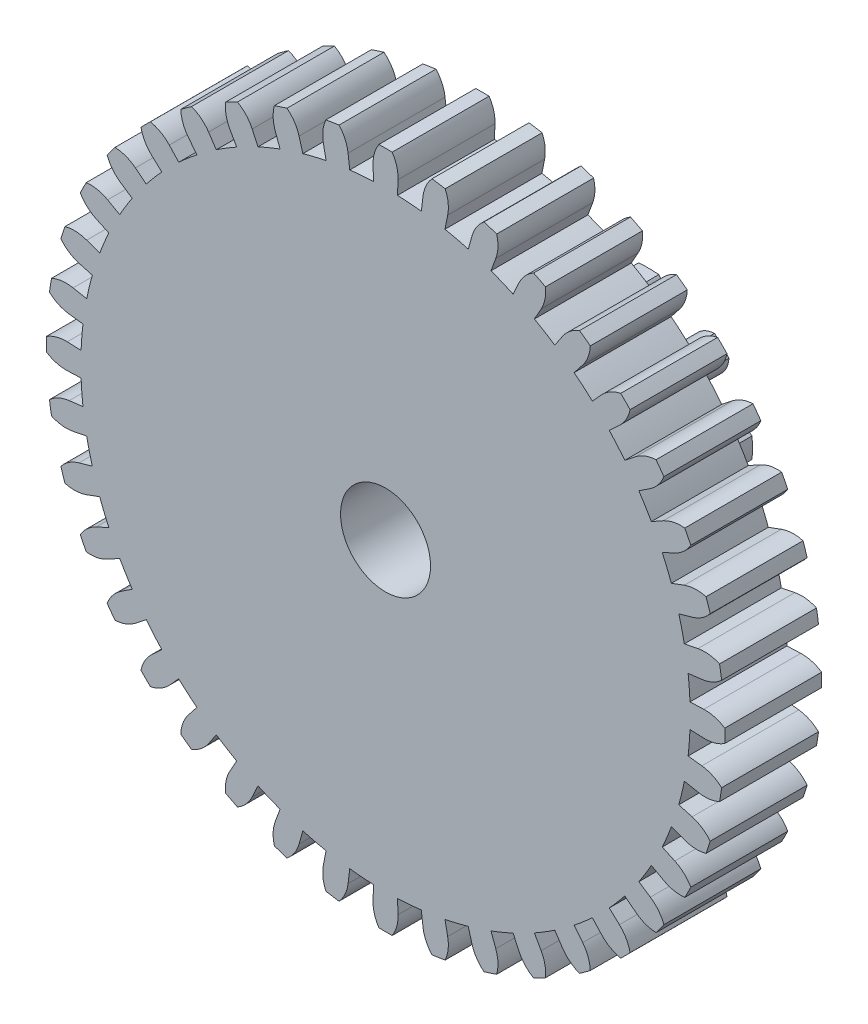
SolidWorks part; units mm, degrees
ref_plane "Front Plane" through (0, 0, 0) normal (0, 0, 1) x (1, 0, 0)
ref_plane "Top Plane" through (0, 0, 0) normal (0, 1, 0) x (1, 0, 0)
ref_plane "Right Plane" through (0, 0, 0) normal (1, 0, 0) x (0, 0, -1)
sketch "Sketch1" plane through (0, 0, 0) normal (0, 0, 1) x (1, 0, 0)
  line L0 (0, 0) -> (4.9, 0) construction
  line L1 (0, 0) -> (4.3864, 0.3452) construction
  line L2 (0, 0) -> (4.8962, 0.1924) construction
  line L3 (0, 0) -> (4.8991, 0.0962) construction
  line L4 (4.3966, 0.1727) -> (4.5965, 0.1806)
  line L5 (4.3966, -0.1727) -> (4.5965, -0.1806)
  line L6 (4.3695, -0.5172) -> (4.5681, -0.5407)
  line L7 (4.3155, -0.8584) -> (4.5116, -0.8974)
  line L8 (4.2348, -1.1943) -> (4.4273, -1.2486)
  line L9 (4.128, -1.5229) -> (4.3157, -1.5921)
  line L10 (3.9958, -1.8421) -> (4.1775, -1.9258)
  line L11 (3.839, -2.1499) -> (4.0135, -2.2477)
  line L12 (3.6585, -2.4445) -> (3.8248, -2.5556)
  line L13 (3.4554, -2.724) -> (3.6125, -2.8478)
  line L14 (3.231, -2.9867) -> (3.3779, -3.1225)
  line L15 (2.9867, -3.231) -> (3.1225, -3.3779)
  line L16 (2.724, -3.4554) -> (2.8478, -3.6125)
  line L17 (2.4445, -3.6585) -> (2.5556, -3.8248)
  line L18 (2.1499, -3.839) -> (2.2477, -4.0135)
  line L19 (1.8421, -3.9958) -> (1.9258, -4.1775)
  line L20 (1.5229, -4.128) -> (1.5921, -4.3157)
  line L21 (1.1943, -4.2348) -> (1.2486, -4.4273)
  line L22 (0.8584, -4.3155) -> (0.8974, -4.5116)
  line L23 (0.5172, -4.3695) -> (0.5407, -4.5681)
  line L24 (0.1727, -4.3966) -> (0.1806, -4.5965)
  line L25 (-0.1727, -4.3966) -> (-0.1806, -4.5965)
  line L26 (-0.5172, -4.3695) -> (-0.5407, -4.5681)
  line L27 (-0.8584, -4.3155) -> (-0.8974, -4.5116)
  line L28 (-1.1943, -4.2348) -> (-1.2486, -4.4273)
  line L29 (-1.5229, -4.128) -> (-1.5921, -4.3157)
  line L30 (-1.8421, -3.9958) -> (-1.9258, -4.1775)
  line L31 (-2.1499, -3.839) -> (-2.2477, -4.0135)
  line L32 (-2.4445, -3.6585) -> (-2.5556, -3.8248)
  line L33 (-2.724, -3.4554) -> (-2.8478, -3.6125)
  line L34 (-2.9867, -3.231) -> (-3.1225, -3.3779)
  line L35 (-3.231, -2.9867) -> (-3.3779, -3.1225)
  line L36 (-3.4554, -2.724) -> (-3.6125, -2.8478)
  line L37 (-3.6585, -2.4445) -> (-3.8248, -2.5556)
  line L38 (-3.839, -2.1499) -> (-4.0135, -2.2477)
  line L39 (-3.9958, -1.8421) -> (-4.1775, -1.9258)
  line L40 (-4.128, -1.5229) -> (-4.3157, -1.5921)
  line L41 (-4.2348, -1.1943) -> (-4.4273, -1.2486)
  line L42 (-4.3155, -0.8584) -> (-4.5116, -0.8974)
  line L43 (-4.3695, -0.5172) -> (-4.5681, -0.5407)
  line L44 (-4.3966, -0.1727) -> (-4.5965, -0.1806)
  line L45 (-4.3966, 0.1727) -> (-4.5965, 0.1806)
  line L46 (-4.3695, 0.5172) -> (-4.5681, 0.5407)
  line L47 (-4.3155, 0.8584) -> (-4.5116, 0.8974)
  line L48 (-4.2348, 1.1943) -> (-4.4273, 1.2486)
  line L49 (-4.128, 1.5229) -> (-4.3157, 1.5921)
  line L50 (-3.9958, 1.8421) -> (-4.1775, 1.9258)
  line L51 (-3.839, 2.1499) -> (-4.0135, 2.2477)
  line L52 (-3.6585, 2.4445) -> (-3.8248, 2.5556)
  line L53 (-3.4554, 2.724) -> (-3.6125, 2.8478)
  line L54 (-3.231, 2.9867) -> (-3.3779, 3.1225)
  line L55 (-2.9867, 3.231) -> (-3.1225, 3.3779)
  line L56 (-2.724, 3.4554) -> (-2.8478, 3.6125)
  line L57 (-2.4445, 3.6585) -> (-2.5556, 3.8248)
  line L58 (-2.1499, 3.839) -> (-2.2477, 4.0135)
  line L59 (-1.8421, 3.9958) -> (-1.9258, 4.1775)
  line L60 (-1.5229, 4.128) -> (-1.5921, 4.3157)
  line L61 (-1.1943, 4.2348) -> (-1.2486, 4.4273)
  line L62 (-0.8584, 4.3155) -> (-0.8974, 4.5116)
  line L63 (-0.5172, 4.3695) -> (-0.5407, 4.5681)
  line L64 (-0.1727, 4.3966) -> (-0.1806, 4.5965)
  line L65 (0.1727, 4.3966) -> (0.1806, 4.5965)
  line L66 (0.5172, 4.3695) -> (0.5407, 4.5681)
  line L67 (0.8584, 4.3155) -> (0.8974, 4.5116)
  line L68 (1.1943, 4.2348) -> (1.2486, 4.4273)
  line L69 (1.5229, 4.128) -> (1.5921, 4.3157)
  line L70 (1.8421, 3.9958) -> (1.9258, 4.1775)
  line L71 (2.1499, 3.839) -> (2.2477, 4.0135)
  line L72 (2.4445, 3.6585) -> (2.5556, 3.8248)
  line L73 (2.724, 3.4554) -> (2.8478, 3.6125)
  line L74 (2.9867, 3.231) -> (3.1225, 3.3779)
  line L75 (3.231, 2.9867) -> (3.3779, 3.1225)
  line L76 (3.4554, 2.724) -> (3.6125, 2.8478)
  line L77 (3.6585, 2.4445) -> (3.8248, 2.5556)
  line L78 (3.839, 2.1499) -> (4.0135, 2.2477)
  line L79 (3.9958, 1.8421) -> (4.1775, 1.9258)
  line L80 (4.128, 1.5229) -> (4.3157, 1.5921)
  line L81 (4.2348, 1.1943) -> (4.4273, 1.2486)
  line L82 (4.3155, 0.8584) -> (4.5116, 0.8974)
  line L83 (4.3695, 0.5172) -> (4.5681, 0.5407)
  arc A0 (4.8991, -0.0962) -> (4.8991, 0.0962) centre (0, 0) ccw
  circle A1 centre (0, 0) radius 4.6 construction
  circle A2 centre (0, 0) radius 4.4 construction
  arc A3 (4.8991, 0.0962) -> (4.5965, 0.1806) centre (4.6166, -0.3319) ccw
  circle A4 centre (0, 0) radius 4.9 construction
  arc A5 (4.3864, 0.3452) -> (4.3966, 0.1727) centre (0, 0) cw
  arc A6 (4.3864, -0.3452) -> (4.3966, -0.1727) centre (0, 0) ccw
  arc A7 (4.8991, -0.0962) -> (4.5965, -0.1806) centre (4.6166, 0.3319) cw
  arc A8 (4.3864, -0.3452) -> (4.3695, -0.5172) centre (0, 0) cw
  arc A9 (4.8538, -0.6714) -> (4.5681, -0.5407) centre (4.5078, -1.05) ccw
  arc A10 (4.8237, -0.8614) -> (4.8538, -0.6714) centre (0, 0) ccw
  arc A11 (4.8237, -0.8614) -> (4.5116, -0.8974) centre (4.6117, -0.3944) cw
  arc A12 (4.2784, -1.0272) -> (4.3155, -0.8584) centre (0, 0) ccw
  arc A13 (4.2784, -1.0272) -> (4.2348, -1.1943) centre (0, 0) cw
  arc A14 (4.689, -1.4224) -> (4.4273, -1.2486) centre (4.2881, -1.7423) ccw
  arc A15 (4.6295, -1.6054) -> (4.689, -1.4224) centre (0, 0) ccw
  arc A16 (4.6295, -1.6054) -> (4.3157, -1.5921) centre (4.4932, -1.1109) cw
  arc A17 (4.0651, -1.6838) -> (4.128, -1.5229) centre (0, 0) ccw
  arc A18 (4.0651, -1.6838) -> (3.9958, -1.8421) centre (0, 0) cw
  arc A19 (4.4088, -2.1384) -> (4.1775, -1.9258) centre (3.9627, -2.3916) ccw
  arc A20 (4.3214, -2.3098) -> (4.4088, -2.1384) centre (0, 0) ccw
  arc A21 (4.3214, -2.3098) -> (4.0135, -2.2477) centre (4.2641, -1.8001) cw
  arc A22 (3.7516, -2.299) -> (3.839, -2.1499) centre (0, 0) ccw
  arc A23 (3.7516, -2.299) -> (3.6585, -2.4445) centre (0, 0) cw
  arc A24 (4.02, -2.8018) -> (3.8248, -2.5556) centre (3.5398, -2.9821) ccw
  arc A25 (3.9069, -2.9574) -> (4.02, -2.8018) centre (0, 0) ccw
  arc A26 (3.9069, -2.9574) -> (3.6125, -2.8478) centre (3.93, -2.445) cw
  arc A27 (3.3458, -2.8576) -> (3.4554, -2.724) centre (0, 0) ccw
  arc A28 (3.3458, -2.8576) -> (3.231, -2.9867) centre (0, 0) cw
  arc A29 (3.5322, -3.3961) -> (3.3779, -3.1225) centre (3.0297, -3.4991) ccw
  arc A30 (3.3961, -3.5322) -> (3.5322, -3.3961) centre (0, 0) ccw
  arc A31 (3.3961, -3.5322) -> (3.1225, -3.3779) centre (3.4991, -3.0297) cw
  arc A32 (2.8576, -3.3458) -> (2.9867, -3.231) centre (0, 0) ccw
  arc A33 (2.8576, -3.3458) -> (2.724, -3.4554) centre (0, 0) cw
  arc A34 (2.9574, -3.9069) -> (2.8478, -3.6125) centre (2.445, -3.93) ccw
  arc A35 (2.8018, -4.02) -> (2.9574, -3.9069) centre (0, 0) ccw
  arc A36 (2.8018, -4.02) -> (2.5556, -3.8248) centre (2.9821, -3.5398) cw
  arc A37 (2.299, -3.7516) -> (2.4445, -3.6585) centre (0, 0) ccw
  arc A38 (2.299, -3.7516) -> (2.1499, -3.839) centre (0, 0) cw
  arc A39 (2.3098, -4.3214) -> (2.2477, -4.0135) centre (1.8001, -4.2641) ccw
  arc A40 (2.1384, -4.4088) -> (2.3098, -4.3214) centre (0, 0) ccw
  arc A41 (2.1384, -4.4088) -> (1.9258, -4.1775) centre (2.3916, -3.9627) cw
  arc A42 (1.6838, -4.0651) -> (1.8421, -3.9958) centre (0, 0) ccw
  arc A43 (1.6838, -4.0651) -> (1.5229, -4.128) centre (0, 0) cw
  arc A44 (1.6054, -4.6295) -> (1.5921, -4.3157) centre (1.1109, -4.4932) ccw
  arc A45 (1.4224, -4.689) -> (1.6054, -4.6295) centre (0, 0) ccw
  arc A46 (1.4224, -4.689) -> (1.2486, -4.4273) centre (1.7423, -4.2881) cw
  arc A47 (1.0272, -4.2784) -> (1.1943, -4.2348) centre (0, 0) ccw
  arc A48 (1.0272, -4.2784) -> (0.8584, -4.3155) centre (0, 0) cw
  arc A49 (0.8614, -4.8237) -> (0.8974, -4.5116) centre (0.3944, -4.6117) ccw
  arc A50 (0.6714, -4.8538) -> (0.8614, -4.8237) centre (0, 0) ccw
  arc A51 (0.6714, -4.8538) -> (0.5407, -4.5681) centre (1.05, -4.5078) cw
  arc A52 (0.3452, -4.3864) -> (0.5172, -4.3695) centre (0, 0) ccw
  arc A53 (0.3452, -4.3864) -> (0.1727, -4.3966) centre (0, 0) cw
  arc A54 (0.0962, -4.8991) -> (0.1806, -4.5965) centre (-0.3319, -4.6166) ccw
  arc A55 (-0.0962, -4.8991) -> (0.0962, -4.8991) centre (0, 0) ccw
  arc A56 (-0.0962, -4.8991) -> (-0.1806, -4.5965) centre (0.3319, -4.6166) cw
  arc A57 (-0.3452, -4.3864) -> (-0.1727, -4.3966) centre (0, 0) ccw
  arc A58 (-0.3452, -4.3864) -> (-0.5172, -4.3695) centre (0, 0) cw
  arc A59 (-0.6714, -4.8538) -> (-0.5407, -4.5681) centre (-1.05, -4.5078) ccw
  arc A60 (-0.8614, -4.8237) -> (-0.6714, -4.8538) centre (0, 0) ccw
  arc A61 (-0.8614, -4.8237) -> (-0.8974, -4.5116) centre (-0.3944, -4.6117) cw
  arc A62 (-1.0272, -4.2784) -> (-0.8584, -4.3155) centre (0, 0) ccw
  arc A63 (-1.0272, -4.2784) -> (-1.1943, -4.2348) centre (0, 0) cw
  arc A64 (-1.4224, -4.689) -> (-1.2486, -4.4273) centre (-1.7423, -4.2881) ccw
  arc A65 (-1.6054, -4.6295) -> (-1.4224, -4.689) centre (0, 0) ccw
  arc A66 (-1.6054, -4.6295) -> (-1.5921, -4.3157) centre (-1.1109, -4.4932) cw
  arc A67 (-1.6838, -4.0651) -> (-1.5229, -4.128) centre (0, 0) ccw
  arc A68 (-1.6838, -4.0651) -> (-1.8421, -3.9958) centre (0, 0) cw
  arc A69 (-2.1384, -4.4088) -> (-1.9258, -4.1775) centre (-2.3916, -3.9627) ccw
  arc A70 (-2.3098, -4.3214) -> (-2.1384, -4.4088) centre (0, 0) ccw
  arc A71 (-2.3098, -4.3214) -> (-2.2477, -4.0135) centre (-1.8001, -4.2641) cw
  arc A72 (-2.299, -3.7516) -> (-2.1499, -3.839) centre (0, 0) ccw
  arc A73 (-2.299, -3.7516) -> (-2.4445, -3.6585) centre (0, 0) cw
  arc A74 (-2.8018, -4.02) -> (-2.5556, -3.8248) centre (-2.9821, -3.5398) ccw
  arc A75 (-2.9574, -3.9069) -> (-2.8018, -4.02) centre (0, 0) ccw
  arc A76 (-2.9574, -3.9069) -> (-2.8478, -3.6125) centre (-2.445, -3.93) cw
  arc A77 (-2.8576, -3.3458) -> (-2.724, -3.4554) centre (0, 0) ccw
  arc A78 (-2.8576, -3.3458) -> (-2.9867, -3.231) centre (0, 0) cw
  arc A79 (-3.3961, -3.5322) -> (-3.1225, -3.3779) centre (-3.4991, -3.0297) ccw
  arc A80 (-3.5322, -3.3961) -> (-3.3961, -3.5322) centre (0, 0) ccw
  arc A81 (-3.5322, -3.3961) -> (-3.3779, -3.1225) centre (-3.0297, -3.4991) cw
  arc A82 (-3.3458, -2.8576) -> (-3.231, -2.9867) centre (0, 0) ccw
  arc A83 (-3.3458, -2.8576) -> (-3.4554, -2.724) centre (0, 0) cw
  arc A84 (-3.9069, -2.9574) -> (-3.6125, -2.8478) centre (-3.93, -2.445) ccw
  arc A85 (-4.02, -2.8018) -> (-3.9069, -2.9574) centre (0, 0) ccw
  arc A86 (-4.02, -2.8018) -> (-3.8248, -2.5556) centre (-3.5398, -2.9821) cw
  arc A87 (-3.7516, -2.299) -> (-3.6585, -2.4445) centre (0, 0) ccw
  arc A88 (-3.7516, -2.299) -> (-3.839, -2.1499) centre (0, 0) cw
  arc A89 (-4.3214, -2.3098) -> (-4.0135, -2.2477) centre (-4.2641, -1.8001) ccw
  arc A90 (-4.4088, -2.1384) -> (-4.3214, -2.3098) centre (0, 0) ccw
  arc A91 (-4.4088, -2.1384) -> (-4.1775, -1.9258) centre (-3.9627, -2.3916) cw
  arc A92 (-4.0651, -1.6838) -> (-3.9958, -1.8421) centre (0, 0) ccw
  arc A93 (-4.0651, -1.6838) -> (-4.128, -1.5229) centre (0, 0) cw
  arc A94 (-4.6295, -1.6054) -> (-4.3157, -1.5921) centre (-4.4932, -1.1109) ccw
  arc A95 (-4.689, -1.4224) -> (-4.6295, -1.6054) centre (0, 0) ccw
  arc A96 (-4.689, -1.4224) -> (-4.4273, -1.2486) centre (-4.2881, -1.7423) cw
  arc A97 (-4.2784, -1.0272) -> (-4.2348, -1.1943) centre (0, 0) ccw
  arc A98 (-4.2784, -1.0272) -> (-4.3155, -0.8584) centre (0, 0) cw
  arc A99 (-4.8237, -0.8614) -> (-4.5116, -0.8974) centre (-4.6117, -0.3944) ccw
  arc A100 (-4.8538, -0.6714) -> (-4.8237, -0.8614) centre (0, 0) ccw
  arc A101 (-4.8538, -0.6714) -> (-4.5681, -0.5407) centre (-4.5078, -1.05) cw
  arc A102 (-4.3864, -0.3452) -> (-4.3695, -0.5172) centre (0, 0) ccw
  arc A103 (-4.3864, -0.3452) -> (-4.3966, -0.1727) centre (0, 0) cw
  arc A104 (-4.8991, -0.0962) -> (-4.5965, -0.1806) centre (-4.6166, 0.3319) ccw
  arc A105 (-4.8991, 0.0962) -> (-4.8991, -0.0962) centre (0, 0) ccw
  arc A106 (-4.8991, 0.0962) -> (-4.5965, 0.1806) centre (-4.6166, -0.3319) cw
  arc A107 (-4.3864, 0.3452) -> (-4.3966, 0.1727) centre (0, 0) ccw
  arc A108 (-4.3864, 0.3452) -> (-4.3695, 0.5172) centre (0, 0) cw
  arc A109 (-4.8538, 0.6714) -> (-4.5681, 0.5407) centre (-4.5078, 1.05) ccw
  arc A110 (-4.8237, 0.8614) -> (-4.8538, 0.6714) centre (0, 0) ccw
  arc A111 (-4.8237, 0.8614) -> (-4.5116, 0.8974) centre (-4.6117, 0.3944) cw
  arc A112 (-4.2784, 1.0272) -> (-4.3155, 0.8584) centre (0, 0) ccw
  arc A113 (-4.2784, 1.0272) -> (-4.2348, 1.1943) centre (0, 0) cw
  arc A114 (-4.689, 1.4224) -> (-4.4273, 1.2486) centre (-4.2881, 1.7423) ccw
  arc A115 (-4.6295, 1.6054) -> (-4.689, 1.4224) centre (0, 0) ccw
  arc A116 (-4.6295, 1.6054) -> (-4.3157, 1.5921) centre (-4.4932, 1.1109) cw
  arc A117 (-4.0651, 1.6838) -> (-4.128, 1.5229) centre (0, 0) ccw
  arc A118 (-4.0651, 1.6838) -> (-3.9958, 1.8421) centre (0, 0) cw
  arc A119 (-4.4088, 2.1384) -> (-4.1775, 1.9258) centre (-3.9627, 2.3916) ccw
  arc A120 (-4.3214, 2.3098) -> (-4.4088, 2.1384) centre (0, 0) ccw
  arc A121 (-4.3214, 2.3098) -> (-4.0135, 2.2477) centre (-4.2641, 1.8001) cw
  arc A122 (-3.7516, 2.299) -> (-3.839, 2.1499) centre (0, 0) ccw
  arc A123 (-3.7516, 2.299) -> (-3.6585, 2.4445) centre (0, 0) cw
  arc A124 (-4.02, 2.8018) -> (-3.8248, 2.5556) centre (-3.5398, 2.9821) ccw
  arc A125 (-3.9069, 2.9574) -> (-4.02, 2.8018) centre (0, 0) ccw
  arc A126 (-3.9069, 2.9574) -> (-3.6125, 2.8478) centre (-3.93, 2.445) cw
  arc A127 (-3.3458, 2.8576) -> (-3.4554, 2.724) centre (0, 0) ccw
  arc A128 (-3.3458, 2.8576) -> (-3.231, 2.9867) centre (0, 0) cw
  arc A129 (-3.5322, 3.3961) -> (-3.3779, 3.1225) centre (-3.0297, 3.4991) ccw
  arc A130 (-3.3961, 3.5322) -> (-3.5322, 3.3961) centre (0, 0) ccw
  arc A131 (-3.3961, 3.5322) -> (-3.1225, 3.3779) centre (-3.4991, 3.0297) cw
  arc A132 (-2.8576, 3.3458) -> (-2.9867, 3.231) centre (0, 0) ccw
  arc A133 (-2.8576, 3.3458) -> (-2.724, 3.4554) centre (0, 0) cw
  arc A134 (-2.9574, 3.9069) -> (-2.8478, 3.6125) centre (-2.445, 3.93) ccw
  arc A135 (-2.8018, 4.02) -> (-2.9574, 3.9069) centre (0, 0) ccw
  arc A136 (-2.8018, 4.02) -> (-2.5556, 3.8248) centre (-2.9821, 3.5398) cw
  arc A137 (-2.299, 3.7516) -> (-2.4445, 3.6585) centre (0, 0) ccw
  arc A138 (-2.299, 3.7516) -> (-2.1499, 3.839) centre (0, 0) cw
  arc A139 (-2.3098, 4.3214) -> (-2.2477, 4.0135) centre (-1.8001, 4.2641) ccw
  arc A140 (-2.1384, 4.4088) -> (-2.3098, 4.3214) centre (0, 0) ccw
  arc A141 (-2.1384, 4.4088) -> (-1.9258, 4.1775) centre (-2.3916, 3.9627) cw
  arc A142 (-1.6838, 4.0651) -> (-1.8421, 3.9958) centre (0, 0) ccw
  arc A143 (-1.6838, 4.0651) -> (-1.5229, 4.128) centre (0, 0) cw
  arc A144 (-1.6054, 4.6295) -> (-1.5921, 4.3157) centre (-1.1109, 4.4932) ccw
  arc A145 (-1.4224, 4.689) -> (-1.6054, 4.6295) centre (0, 0) ccw
  arc A146 (-1.4224, 4.689) -> (-1.2486, 4.4273) centre (-1.7423, 4.2881) cw
  arc A147 (-1.0272, 4.2784) -> (-1.1943, 4.2348) centre (0, 0) ccw
  arc A148 (-1.0272, 4.2784) -> (-0.8584, 4.3155) centre (0, 0) cw
  arc A149 (-0.8614, 4.8237) -> (-0.8974, 4.5116) centre (-0.3944, 4.6117) ccw
  arc A150 (-0.6714, 4.8538) -> (-0.8614, 4.8237) centre (0, 0) ccw
  arc A151 (-0.6714, 4.8538) -> (-0.5407, 4.5681) centre (-1.05, 4.5078) cw
  arc A152 (-0.3452, 4.3864) -> (-0.5172, 4.3695) centre (0, 0) ccw
  arc A153 (-0.3452, 4.3864) -> (-0.1727, 4.3966) centre (0, 0) cw
  arc A154 (-0.0962, 4.8991) -> (-0.1806, 4.5965) centre (0.3319, 4.6166) ccw
  arc A155 (0.0962, 4.8991) -> (-0.0962, 4.8991) centre (0, 0) ccw
  arc A156 (0.0962, 4.8991) -> (0.1806, 4.5965) centre (-0.3319, 4.6166) cw
  arc A157 (0.3452, 4.3864) -> (0.1727, 4.3966) centre (0, 0) ccw
  arc A158 (0.3452, 4.3864) -> (0.5172, 4.3695) centre (0, 0) cw
  arc A159 (0.6714, 4.8538) -> (0.5407, 4.5681) centre (1.05, 4.5078) ccw
  arc A160 (0.8614, 4.8237) -> (0.6714, 4.8538) centre (0, 0) ccw
  arc A161 (0.8614, 4.8237) -> (0.8974, 4.5116) centre (0.3944, 4.6117) cw
  arc A162 (1.0272, 4.2784) -> (0.8584, 4.3155) centre (0, 0) ccw
  arc A163 (1.0272, 4.2784) -> (1.1943, 4.2348) centre (0, 0) cw
  arc A164 (1.4224, 4.689) -> (1.2486, 4.4273) centre (1.7423, 4.2881) ccw
  arc A165 (1.6054, 4.6295) -> (1.4224, 4.689) centre (0, 0) ccw
  arc A166 (1.6054, 4.6295) -> (1.5921, 4.3157) centre (1.1109, 4.4932) cw
  arc A167 (1.6838, 4.0651) -> (1.5229, 4.128) centre (0, 0) ccw
  arc A168 (1.6838, 4.0651) -> (1.8421, 3.9958) centre (0, 0) cw
  arc A169 (2.1384, 4.4088) -> (1.9258, 4.1775) centre (2.3916, 3.9627) ccw
  arc A170 (2.3098, 4.3214) -> (2.1384, 4.4088) centre (0, 0) ccw
  arc A171 (2.3098, 4.3214) -> (2.2477, 4.0135) centre (1.8001, 4.2641) cw
  arc A172 (2.299, 3.7516) -> (2.1499, 3.839) centre (0, 0) ccw
  arc A173 (2.299, 3.7516) -> (2.4445, 3.6585) centre (0, 0) cw
  arc A174 (2.8018, 4.02) -> (2.5556, 3.8248) centre (2.9821, 3.5398) ccw
  arc A175 (2.9574, 3.9069) -> (2.8018, 4.02) centre (0, 0) ccw
  arc A176 (2.9574, 3.9069) -> (2.8478, 3.6125) centre (2.445, 3.93) cw
  arc A177 (2.8576, 3.3458) -> (2.724, 3.4554) centre (0, 0) ccw
  arc A178 (2.8576, 3.3458) -> (2.9867, 3.231) centre (0, 0) cw
  arc A179 (3.3961, 3.5322) -> (3.1225, 3.3779) centre (3.4991, 3.0297) ccw
  arc A180 (3.5322, 3.3961) -> (3.3961, 3.5322) centre (0, 0) ccw
  arc A181 (3.5322, 3.3961) -> (3.3779, 3.1225) centre (3.0297, 3.4991) cw
  arc A182 (3.3458, 2.8576) -> (3.231, 2.9867) centre (0, 0) ccw
  arc A183 (3.3458, 2.8576) -> (3.4554, 2.724) centre (0, 0) cw
  arc A184 (3.9069, 2.9574) -> (3.6125, 2.8478) centre (3.93, 2.445) ccw
  arc A185 (4.02, 2.8018) -> (3.9069, 2.9574) centre (0, 0) ccw
  arc A186 (4.02, 2.8018) -> (3.8248, 2.5556) centre (3.5398, 2.9821) cw
  arc A187 (3.7516, 2.299) -> (3.6585, 2.4445) centre (0, 0) ccw
  arc A188 (3.7516, 2.299) -> (3.839, 2.1499) centre (0, 0) cw
  arc A189 (4.3214, 2.3098) -> (4.0135, 2.2477) centre (4.2641, 1.8001) ccw
  arc A190 (4.4088, 2.1384) -> (4.3214, 2.3098) centre (0, 0) ccw
  arc A191 (4.4088, 2.1384) -> (4.1775, 1.9258) centre (3.9627, 2.3916) cw
  arc A192 (4.0651, 1.6838) -> (3.9958, 1.8421) centre (0, 0) ccw
  arc A193 (4.0651, 1.6838) -> (4.128, 1.5229) centre (0, 0) cw
  arc A194 (4.6295, 1.6054) -> (4.3157, 1.5921) centre (4.4932, 1.1109) ccw
  arc A195 (4.689, 1.4224) -> (4.6295, 1.6054) centre (0, 0) ccw
  arc A196 (4.689, 1.4224) -> (4.4273, 1.2486) centre (4.2881, 1.7423) cw
  arc A197 (4.2784, 1.0272) -> (4.2348, 1.1943) centre (0, 0) ccw
  arc A198 (4.2784, 1.0272) -> (4.3155, 0.8584) centre (0, 0) cw
  arc A199 (4.8237, 0.8614) -> (4.5116, 0.8974) centre (4.6117, 0.3944) ccw
  arc A200 (4.8538, 0.6714) -> (4.8237, 0.8614) centre (0, 0) ccw
  arc A201 (4.8538, 0.6714) -> (4.5681, 0.5407) centre (4.5078, 1.05) cw
  arc A202 (4.3864, 0.3452) -> (4.3695, 0.5172) centre (0, 0) ccw
  point P411 (0, 0)
  dimension "D1" = 9.8
  dimension "D2" = 9.2
  dimension "D3" = 0.5
  dimension "D4" = 4.5
  dimension "D5" = 2.25
  dimension "D6" = 1.125
extrude "Boss-Extrude1" add sketch "Sketch1" along normal blind 1.4 contours A5 A202 L83 A201 A200 A199 L82 A198 A197 L81 A196 A195 A194 L80 A193 A192 L79 A191 A190 A189 L78 A188 A187 L77 A186 A185 A184 L76 A183 A182 L75 A181 A180 A179 L74 A178 A177 L73 A176 A175 A174 L72 A173 A172 L71 A171 A170 A169 L70 A168 A167
sketch "Sketch3" plane through (0, 0, 0) normal (0, 0, 1) x (1, 0, 0)
  line L0 (0, 0) -> (1.5, 0) construction
  line L1 (0, 0) -> (0.9239, 0.3827) construction
  line L2 (0, 0) -> (1.4712, 0.2926) construction
  line L3 (0, 0) -> (1.4928, 0.147) construction
  line L4 (0.9808, 0.1951) -> (1.1769, 0.2341)
  line L5 (0.9808, -0.1951) -> (1.1769, -0.2341)
  line L6 (0.8315, -0.5556) -> (0.9978, -0.6667)
  line L7 (0.5556, -0.8315) -> (0.6667, -0.9978)
  line L8 (0.1951, -0.9808) -> (0.2341, -1.1769)
  line L9 (-0.1951, -0.9808) -> (-0.2341, -1.1769)
  line L10 (-0.5556, -0.8315) -> (-0.6667, -0.9978)
  line L11 (-0.8315, -0.5556) -> (-0.9978, -0.6667)
  line L12 (-0.9808, -0.1951) -> (-1.1769, -0.2341)
  line L13 (-0.9808, 0.1951) -> (-1.1769, 0.2341)
  line L14 (-0.8315, 0.5556) -> (-0.9978, 0.6667)
  line L15 (-0.5556, 0.8315) -> (-0.6667, 0.9978)
  line L16 (-0.1951, 0.9808) -> (-0.2341, 1.1769)
  line L17 (0.1951, 0.9808) -> (0.2341, 1.1769)
  line L18 (0.5556, 0.8315) -> (0.6667, 0.9978)
  line L19 (0.8315, 0.5556) -> (0.9978, 0.6667)
  circle A0 centre (0, 0) radius 1.5 construction
  circle A1 centre (0, 0) radius 1.2 construction
  circle A2 centre (0, 0) radius 1 construction
  arc A3 (1.4928, 0.147) -> (1.1769, 0.2341) centre (1.2482, -0.1239) ccw
  arc A4 (1.4928, -0.147) -> (1.4928, 0.147) centre (0, 0) ccw
  arc A5 (0.9239, 0.3827) -> (0.9808, 0.1951) centre (0, 0) cw
  arc A6 (0.9239, -0.3827) -> (0.9808, -0.1951) centre (0, 0) ccw
  arc A7 (1.4928, -0.147) -> (1.1769, -0.2341) centre (1.2482, 0.1239) cw
  arc A8 (0.9239, -0.3827) -> (0.8315, -0.5556) centre (0, 0) cw
  arc A9 (1.1595, -0.9516) -> (0.9978, -0.6667) centre (0.795, -0.9702) ccw
  arc A10 (0.9516, -1.1595) -> (0.6667, -0.9978) centre (0.9702, -0.795) cw
  arc A11 (0.3827, -0.9239) -> (0.5556, -0.8315) centre (0, 0) ccw
  arc A12 (0.9516, -1.1595) -> (1.1595, -0.9516) centre (0, 0) ccw
  arc A13 (0.3827, -0.9239) -> (0.1951, -0.9808) centre (0, 0) cw
  arc A14 (0.147, -1.4928) -> (0.2341, -1.1769) centre (-0.1239, -1.2482) ccw
  arc A15 (-0.147, -1.4928) -> (-0.2341, -1.1769) centre (0.1239, -1.2482) cw
  arc A16 (-0.3827, -0.9239) -> (-0.1951, -0.9808) centre (0, 0) ccw
  arc A17 (-0.147, -1.4928) -> (0.147, -1.4928) centre (0, 0) ccw
  arc A18 (-0.3827, -0.9239) -> (-0.5556, -0.8315) centre (0, 0) cw
  arc A19 (-0.9516, -1.1595) -> (-0.6667, -0.9978) centre (-0.9702, -0.795) ccw
  arc A20 (-1.1595, -0.9516) -> (-0.9978, -0.6667) centre (-0.795, -0.9702) cw
  arc A21 (-0.9239, -0.3827) -> (-0.8315, -0.5556) centre (0, 0) ccw
  arc A22 (-1.1595, -0.9516) -> (-0.9516, -1.1595) centre (0, 0) ccw
  arc A23 (-0.9239, -0.3827) -> (-0.9808, -0.1951) centre (0, 0) cw
  arc A24 (-1.4928, -0.147) -> (-1.1769, -0.2341) centre (-1.2482, 0.1239) ccw
  arc A25 (-1.4928, 0.147) -> (-1.1769, 0.2341) centre (-1.2482, -0.1239) cw
  arc A26 (-0.9239, 0.3827) -> (-0.9808, 0.1951) centre (0, 0) ccw
  arc A27 (-1.4928, 0.147) -> (-1.4928, -0.147) centre (0, 0) ccw
  arc A28 (-0.9239, 0.3827) -> (-0.8315, 0.5556) centre (0, 0) cw
  arc A29 (-1.1595, 0.9516) -> (-0.9978, 0.6667) centre (-0.795, 0.9702) ccw
  arc A30 (-0.9516, 1.1595) -> (-0.6667, 0.9978) centre (-0.9702, 0.795) cw
  arc A31 (-0.3827, 0.9239) -> (-0.5556, 0.8315) centre (0, 0) ccw
  arc A32 (-0.9516, 1.1595) -> (-1.1595, 0.9516) centre (0, 0) ccw
  arc A33 (-0.3827, 0.9239) -> (-0.1951, 0.9808) centre (0, 0) cw
  arc A34 (-0.147, 1.4928) -> (-0.2341, 1.1769) centre (0.1239, 1.2482) ccw
  arc A35 (0.147, 1.4928) -> (0.2341, 1.1769) centre (-0.1239, 1.2482) cw
  arc A36 (0.3827, 0.9239) -> (0.1951, 0.9808) centre (0, 0) ccw
  arc A37 (0.147, 1.4928) -> (-0.147, 1.4928) centre (0, 0) ccw
  arc A38 (0.3827, 0.9239) -> (0.5556, 0.8315) centre (0, 0) cw
  arc A39 (0.9516, 1.1595) -> (0.6667, 0.9978) centre (0.9702, 0.795) ccw
  arc A40 (1.1595, 0.9516) -> (0.9978, 0.6667) centre (0.795, 0.9702) cw
  arc A41 (0.9239, 0.3827) -> (0.8315, 0.5556) centre (0, 0) ccw
  arc A42 (1.1595, 0.9516) -> (0.9516, 1.1595) centre (0, 0) ccw
  point P91 (0, 0)
  dimension "D1" = 3
  dimension "D2" = 2.4
  dimension "D3" = 0.5
  dimension "D4" = 22.5
  dimension "D5" = 11.25
  dimension "D6" = 5.625
  dimension "D7" = 8
extrude "Boss-Extrude2" add sketch "Sketch3" against normal blind 2.4 contours A40 A42 A39 L18 A38 A36 L17 A35 A37 A34 L16 A33 A31 L15 A30 A32 A29 L14 A28 A26 L13 A25 A27 A24 L12 A23 A21 L11 A20 A22 A19 L10 A18 A16 L9 A15 A17 A14 L8 A13 A11 L7 A10 A12 A9 L6 A8 A6 L5 A7 A4
sketch "Sketch4" plane through (0, 0, -2.4) normal (0, 0, -1) x (-1, 0, 0)
  circle A0 centre (0, 0) radius 0.65
  dimension "D1" = 1.3
extrude "Cut-Extrude1" cut sketch "Sketch4" against normal blind 10
